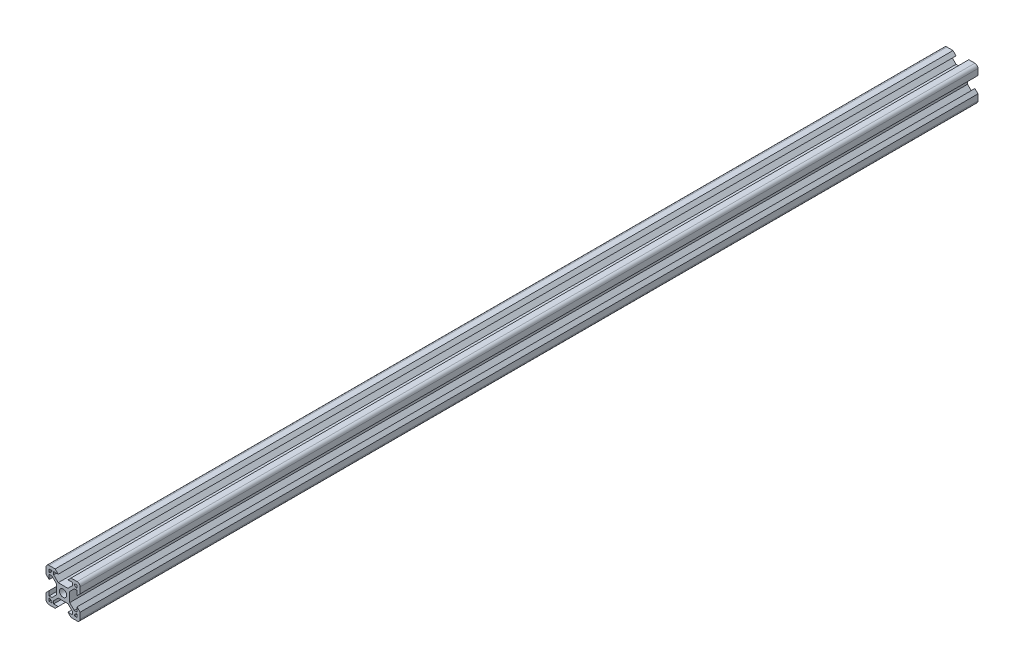
SolidWorks part; units mm, degrees
material "6063-T5"
ref_plane "Plane1" through (0, 0, 0) normal (0, 0, 1) x (1, 0, 0)
ref_plane "Plane2" through (0, 0, 0) normal (0, 1, 0) x (1, 0, 0)
ref_plane "Plane3" through (0, 0, 0) normal (1, 0, 0) x (0, 0, -1)
sketch "Sketch1" plane through (0, 0, 0) normal (0, 0, 1) x (1, 0, 0)
  line L0 (-3.9007, 0) -> (-3.9007, -2.84)
  line L1 (-3.9007, -2.84) -> (-6.56, -5.4993)
  line L2 (-6.56, -5.4993) -> (-8.2, -5.4993)
  line L3 (-8.2, -5.4993) -> (-8.2, -2.84)
  line L4 (-8.2, -2.84) -> (-10, -4.64)
  line L5 (-10, -4.64) -> (-10, -8.2)
  line L6 (0, 0) -> (-17.0509, -17.0509) construction
  line L7 (0, 0) -> (0, -17.0509) construction
  line L8 (0, 0) -> (-30.3777, 0) construction
  line L9 (-4.64, -10) -> (-8.2, -10)
  line L10 (-2.84, -8.2) -> (-4.64, -10)
  line L11 (-5.4993, -8.2) -> (-2.84, -8.2)
  line L12 (-5.4993, -6.56) -> (-5.4993, -8.2)
  line L13 (-2.84, -3.9007) -> (-5.4993, -6.56)
  line L14 (0, -3.9007) -> (-2.84, -3.9007)
  line L15 (-8.2, -8.2) -> (-8.2, -6.5693)
  line L16 (-8.2, -6.5693) -> (-7.63, -6.5693)
  line L17 (-7.63, -6.5693) -> (-6.5693, -7.63)
  line L18 (-6.5693, -7.63) -> (-6.5693, -8.2)
  line L19 (-6.5693, -8.2) -> (-8.2, -8.2)
  line L20 (-3.9007, 0) -> (-3.9007, 2.84)
  line L21 (-3.9007, 2.84) -> (-6.56, 5.4993)
  line L22 (-6.56, 5.4993) -> (-8.2, 5.4993)
  line L23 (-8.2, 5.4993) -> (-8.2, 2.84)
  line L24 (-8.2, 2.84) -> (-10, 4.64)
  line L25 (-10, 4.64) -> (-10, 8.2)
  line L26 (-4.64, 10) -> (-8.2, 10)
  line L27 (-2.84, 8.2) -> (-4.64, 10)
  line L28 (-5.4993, 8.2) -> (-2.84, 8.2)
  line L29 (-5.4993, 6.56) -> (-5.4993, 8.2)
  line L30 (-2.84, 3.9007) -> (-5.4993, 6.56)
  line L31 (0, 3.9007) -> (-2.84, 3.9007)
  line L32 (-8.2, 6.5693) -> (-8.2, 8.2)
  line L33 (-8.2, 8.2) -> (-6.5693, 8.2)
  line L34 (-6.5693, 8.2) -> (-6.5693, 7.63)
  line L35 (-6.5693, 7.63) -> (-7.63, 6.5693)
  line L36 (-7.63, 6.5693) -> (-8.2, 6.5693)
  line L37 (0, 3.9007) -> (2.84, 3.9007)
  line L38 (2.84, 3.9007) -> (5.4993, 6.56)
  line L39 (5.4993, 6.56) -> (5.4993, 8.2)
  line L40 (5.4993, 8.2) -> (2.84, 8.2)
  line L41 (2.84, 8.2) -> (4.64, 10)
  line L42 (4.64, 10) -> (8.2, 10)
  line L43 (10, 4.64) -> (10, 8.2)
  line L44 (8.2, 2.84) -> (10, 4.64)
  line L45 (8.2, 5.4993) -> (8.2, 2.84)
  line L46 (6.56, 5.4993) -> (8.2, 5.4993)
  line L47 (3.9007, 2.84) -> (6.56, 5.4993)
  line L48 (3.9007, 0) -> (3.9007, 2.84)
  line L49 (6.5693, 8.2) -> (8.2, 8.2)
  line L50 (8.2, 8.2) -> (8.2, 6.5693)
  line L51 (8.2, 6.5693) -> (7.63, 6.5693)
  line L52 (7.63, 6.5693) -> (6.5693, 7.63)
  line L53 (6.5693, 7.63) -> (6.5693, 8.2)
  line L54 (3.9007, 0) -> (3.9007, -2.84)
  line L55 (3.9007, -2.84) -> (6.56, -5.4993)
  line L56 (6.56, -5.4993) -> (8.2, -5.4993)
  line L57 (8.2, -5.4993) -> (8.2, -2.84)
  line L58 (8.2, -2.84) -> (10, -4.64)
  line L59 (10, -4.64) -> (10, -8.2)
  line L60 (4.64, -10) -> (8.2, -10)
  line L61 (2.84, -8.2) -> (4.64, -10)
  line L62 (5.4993, -8.2) -> (2.84, -8.2)
  line L63 (5.4993, -6.56) -> (5.4993, -8.2)
  line L64 (2.84, -3.9007) -> (5.4993, -6.56)
  line L65 (0, -3.9007) -> (2.84, -3.9007)
  line L66 (8.2, -6.5693) -> (8.2, -8.2)
  line L67 (8.2, -8.2) -> (6.5693, -8.2)
  line L68 (6.5693, -8.2) -> (6.5693, -7.63)
  line L69 (6.5693, -7.63) -> (7.63, -6.5693)
  line L70 (7.63, -6.5693) -> (8.2, -6.5693)
  circle A0 centre (0, 0) radius 2.1
  arc A1 (-10, -8.2) -> (-8.2, -10) centre (-8.2, -8.2) ccw
  arc A2 (-8.2, 10) -> (-10, 8.2) centre (-8.2, 8.2) ccw
  arc A3 (10, 8.2) -> (8.2, 10) centre (8.2, 8.2) ccw
  arc A4 (8.2, -10) -> (10, -8.2) centre (8.2, -8.2) ccw
  point P23 (-7.0997, -7.0997)
  dimension "D4" = 4.2
  dimension "D1" = 45
  dimension "D2" = 5.68
  dimension "D3" = 1.64
  dimension "D5" = 1.5
  dimension "D6" = 20
  dimension "D7" = 1.8
  dimension "D8" = 1.07
  dimension "D9" = 4
extrude "Extrude1" add sketch "Sketch1" along normal mid plane 525.9
